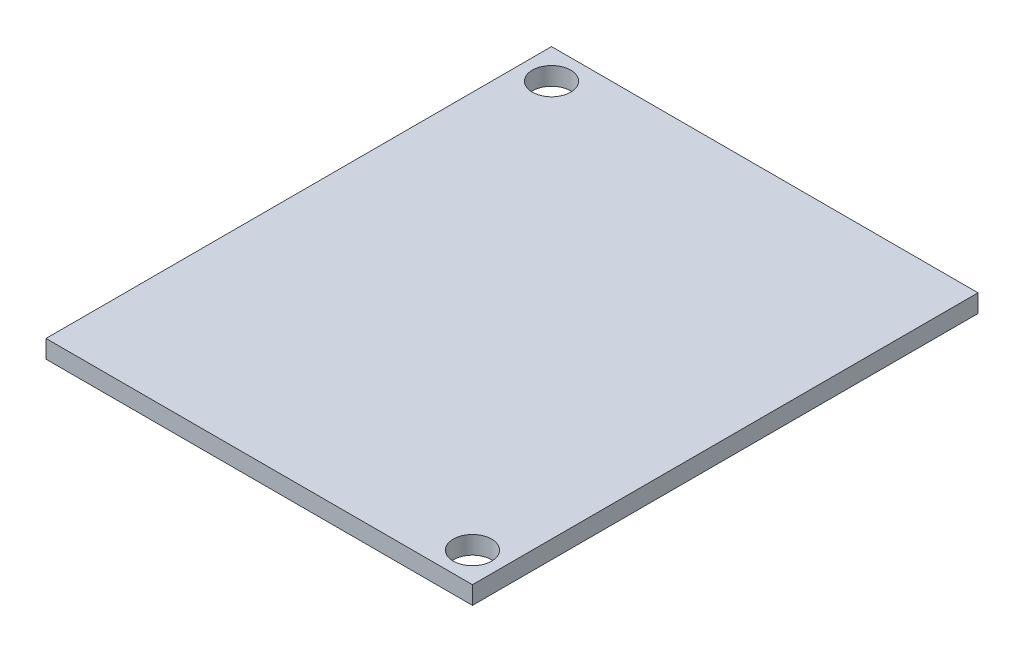
SolidWorks part; units mm, degrees
ref_plane "Front Plane" through (0, 0, 0) normal (0, 0, 1) x (1, 0, 0)
ref_plane "Top Plane" through (0, 0, 0) normal (0, 1, 0) x (1, 0, 0)
ref_plane "Right Plane" through (0, 0, 0) normal (1, 0, 0) x (0, 0, -1)
sketch "Sketch1" plane through (0, 0, 0) normal (0, 1, 0) x (1, 0, 0)
  line L1 (17.8, -21.1) -> (-17.8, -21.1)
  line L2 (17.8, -21.1) -> (17.8, 21.1)
  line L3 (17.8, 21.1) -> (-17.8, 21.1)
  line L4 (-17.8, -21.1) -> (-17.8, 21.1)
  line L5 (17.8, -21.1) -> (-17.8, 21.1) construction
  line L6 (17.8, 21.1) -> (-17.8, -21.1) construction
  circle A0 centre (-15.3, 18.6) radius 1.6
  circle A1 centre (15.3, -18.6) radius 1.6
  point P0 (0, 0)
  point P6 (-15.3, 18.6)
  point P9 (15.3, -18.6)
  dimension "D5" = 3.2
  dimension "D1" = 35.6
  dimension "D2" = 42.2
  dimension "D3" = 2.5
  dimension "D4" = 2.5
  dimension "D6" = 2.5
  dimension "D7" = 2.5
extrude "Boss-Extrude1" add sketch "Sketch1" along normal blind 1.5
